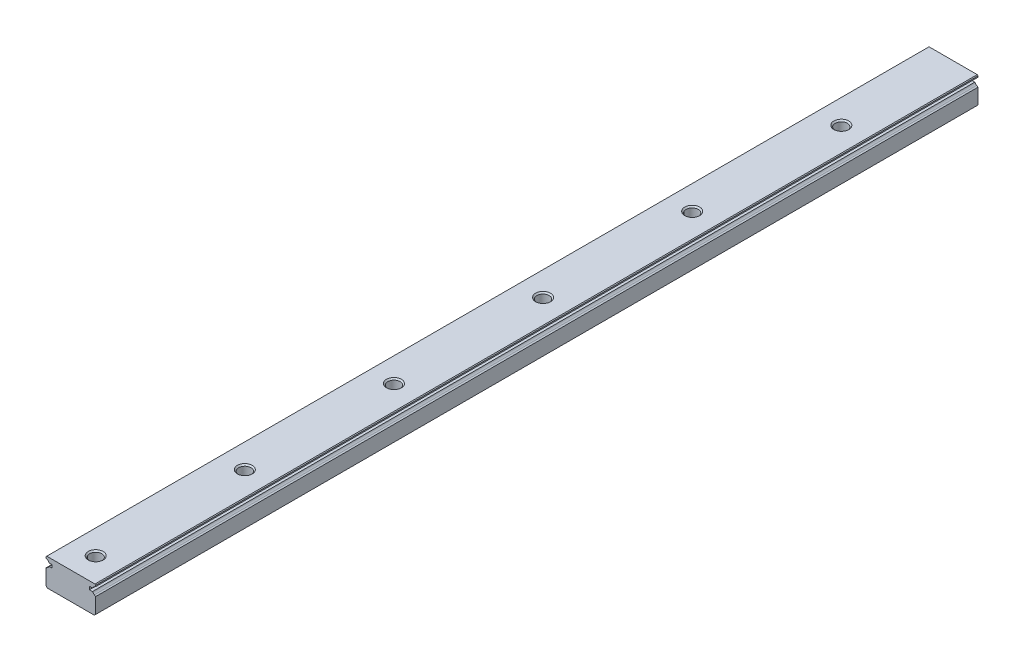
SolidWorks part; units mm, degrees
ref_plane "Plan de face" through (0, 0, 0) normal (0, 0, 1) x (1, 0, 0)
ref_plane "Plan de dessus" through (0, 0, 0) normal (0, 1, 0) x (1, 0, 0)
ref_plane "Plan de droite" through (0, 0, 0) normal (1, 0, 0) x (0, 0, -1)
ref_plane "Plan1" through (0, 0, 0) normal (0, -1, 0) x (1, 0, 0)
sketch "Esquisse1" plane through (0, 0, 0) normal (0, -1, 0) x (1, 0, 0)
  line L0 (-10, -105) -> (10, -105)
  line L1 (10, -105) -> (10, 250)
  line L2 (10, 250) -> (-10, 250)
  line L3 (-10, 250) -> (-10, -105)
  dimension "D1" = 355
  dimension "D2" = 20
extrude "Boss.-Extru.1" add sketch "Esquisse1" against normal blind 11
sketch "Esquisse2" plane through (0, 0, -105) normal (0, 0, -1) x (-1, 0, 0)
  line L0 (10, 7.9) -> (10, 10.2238)
  line L1 (10, 10.2238) -> (9.44, 9.9006)
  line L2 (8.7177, 9.1) -> (7.5, 9.1)
  line L3 (7.5, 9.1) -> (7.5, 7.9)
  line L4 (7.5, 7.9) -> (10, 7.9)
  arc A0 (9.44, 9.9006) -> (8.7177, 9.1) centre (10.315, 8.385) ccw
extrude "Enlèv. mat.-Extru.1" cut sketch "Esquisse2" against normal through all
sketch "Esquisse3" plane through (0, 0, -105) normal (0, 0, -1) x (-1, 0, 0)
  line L0 (9.44, 7.0994) -> (10, 6.7761)
  line L1 (10, 6.7761) -> (10, 7.9)
  line L2 (10, 7.9) -> (8.7177, 7.9)
  arc A0 (8.7177, 7.9) -> (9.44, 7.0994) centre (10.315, 8.615) ccw
extrude "Enlèv. mat.-Extru.2" cut sketch "Esquisse3" against normal through all
sketch "Esquisse4" plane through (0, 0, -105) normal (0, 0, -1) x (-1, 0, 0)
  line L0 (-10, 9.1) -> (-10, 6.7761)
  line L1 (-10, 6.7761) -> (-9.44, 7.0994)
  line L2 (-8.7177, 7.9) -> (-7.5, 7.9)
  line L3 (-7.5, 7.9) -> (-7.5, 9.1)
  line L4 (-7.5, 9.1) -> (-10, 9.1)
  arc A0 (-9.44, 7.0994) -> (-8.7177, 7.9) centre (-10.315, 8.615) ccw
extrude "Enlèv. mat.-Extru.3" cut sketch "Esquisse4" against normal through all
sketch "Esquisse5" plane through (0, 0, -105) normal (0, 0, -1) x (-1, 0, 0)
  line L0 (-9.44, 9.9006) -> (-10, 10.2239)
  line L1 (-10, 10.2239) -> (-10, 9.1)
  line L2 (-10, 9.1) -> (-8.7177, 9.1)
  arc A0 (-8.7177, 9.1) -> (-9.44, 9.9006) centre (-10.315, 8.385) ccw
extrude "Enlèv. mat.-Extru.4" cut sketch "Esquisse5" against normal through all
hole_wizard "Perçage1" positions "Esquisse7" profile "Esquisse6" legacy
sketch "Esquisse7" plane through (0, 11, 0) normal (0, 1, 0) x (1, 0, 0)
  point P0 (0, -180)
  point P1 (0, -120)
  point P2 (0, 60)
  point P3 (0, 180)
sketch "Esquisse6" plane through (0, 11, 180) normal (1, 0, 0) x (0, 0, 1)
  line L0 (0, 0) -> (0, 11)
  line L1 (0, 11) -> (2.4585, 11)
  line L2 (2.4585, 11) -> (2.4585, 0)
  line L3 (2.4585, 0) -> (0, 0)
  line L4 (0, 110) -> (0, -10) construction
  dimension "Diamètre" = 4.917
  dimension "Profondeur" = 11
hole_wizard "Perçage2" positions "Esquisse9" profile "Esquisse8" legacy end condition through all
sketch "Esquisse9" plane through (0, 0, 0) normal (0, -1, 0) x (-1, 0, 0)
  point P0 (0, -240)
  point P1 (0, -60)
  point P2 (0, 0)
  point P3 (0, 120)
  point P4 (0, 240)
sketch "Esquisse8" plane through (0, 0, 240) normal (1, 0, 0) x (0, 0, -1)
  line L0 (0, 0) -> (0, 11)
  line L1 (0, 11) -> (2.4585, 11)
  line L2 (2.4585, 11) -> (2.4585, 0)
  line L3 (2.4585, 0) -> (0, 0)
  line L4 (0, 110) -> (0, -10) construction
  dimension "Diamètre" = 4.917
  dimension "Profondeur" = 11
chamfer "Chanfrein1" distance 0.5415 angle 45 14 edges at (0, 11, -2.4585) (0, 0, -2.4585) (0, 0, -57.5415) (0, 11, 57.5415) (0, 11, -57.5415) (-10, 0, 72.5) (10, 0, 72.5) (0, 0, 182.4585) (0, 0, 57.5415) (0, 0, 122.4585) (0, 11, 122.4585) (0, 11, 237.5415) (0, 0, 237.5415) (0, 11, 182.4585)
chamfer "Chanfrein2" distance 0.3 angle 45 2 edges at (-10, 11, 72.5) (10, 11, 72.5)
pattern_linear "Répétition linéaire1" [suppressed] count 9 spacing 60
